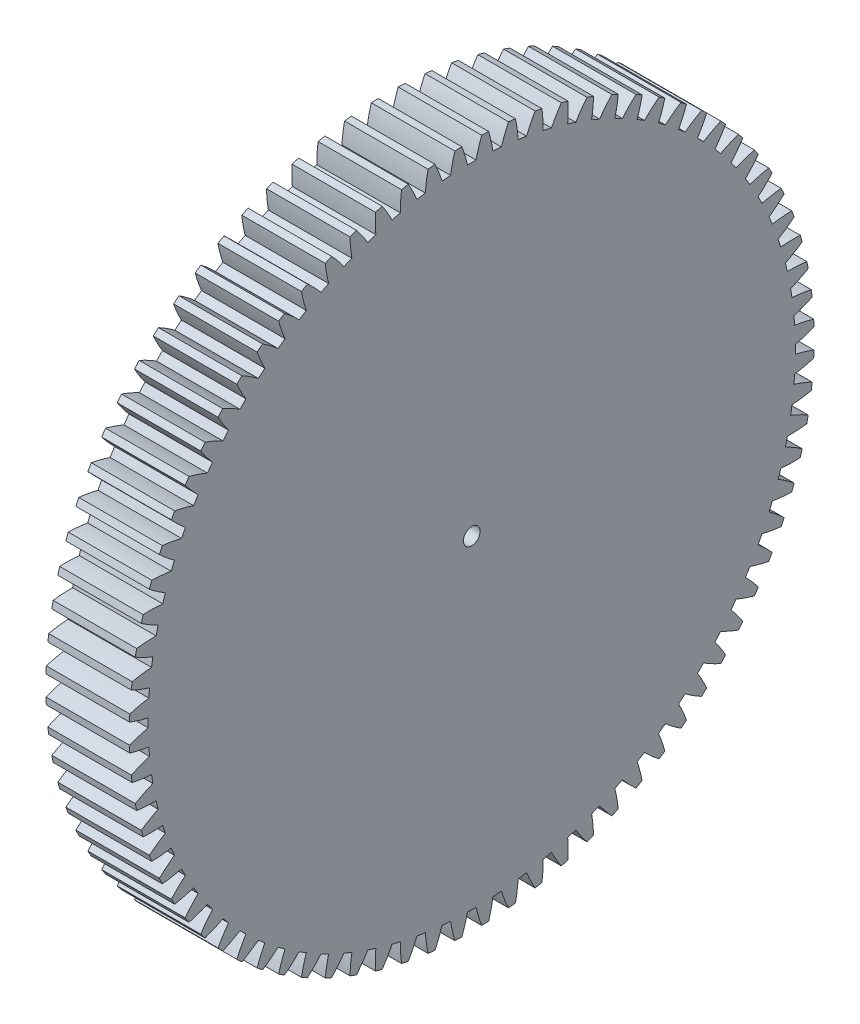
SolidWorks part; units mm, degrees
ref_plane "Plane1" through (0, 0, 0) normal (0, 0, 1) x (1, 0, 0)
ref_plane "Plane2" through (0, 0, 0) normal (0, 1, 0) x (1, 0, 0)
ref_plane "Plane3" through (0, 0, 0) normal (1, 0, 0) x (0, 0, -1)
sketch "HoldingSke" plane through (0, 0, 0) normal (0, 1, 0) x (1, 0, 0)
  line L0 (0, 0) -> (0.1158, -0.6565)
  line L1 (-15, 0) -> (100, 0) construction
  line L2 (0, 0) -> (-2.1039, 2.3779)
  line L3 (0, 0) -> (-11.863, 4.5341)
  line L4 (0, 0) -> (1.4996, 8.5048)
  line L5 (0, 0) -> (-46.8476, -17.4728)
  line L6 (0, 0) -> (-12.4344, -8.3896)
  line L7 (-2.1039, 2.3779) -> (8.6586, 51.2059)
  line L8 (-76.2, 54.61) -> (-75.7, 54.61)
  line L9 (-67.7845, 28.3722) -> (-49.3413, 33.142)
  line L10 (-76.2, 71.12) -> (104.1128, 71.12)
  line L11 (0, 0) -> (-15, 0)
  line L12 (-76.2, 101.6) -> (-76.147, 101.6)
  line L13 (24.9733, 27.94) -> (52.9518, 28.4284)
  line L14 (24.9733, 27.94) -> (24.9743, 27.94)
  line L15 (24.9733, 27.94) -> (100.4006, 29.5858)
  line L16 (-63.627, -1.5) -> (-12.827, -1.5)
  circle A0 centre (0, 0) radius 1.5
  circle A1 centre (0, 0) radius 37.5
  circle A2 centre (0, 0) radius 37.5
  circle A3 centre (0, 0) radius 1.5
  dimension "MHD" = 75
  dimension "Hub_dia" = 75
  dimension "Bore" = 3
  dimension "MBD" = 3
  dimension "Num_teeth" = 80
  dimension "Pitch" = 0.6667
  dimension "Overall_len" = 50
  dimension "Show_teeth" = 80
  dimension "Thickness" = 15
  dimension "OAL" = 50.0001
  dimension "T_dim" = 0.5
  dimension "Ap" = 14.5
  dimension "H" = 19.05
  dimension "Pitch_radius" = 180.3128
  dimension "Width" = 15
  dimension "Backlash" = 0.053
  dimension "Addendum_fac" = 1
  dimension "Dedendum_fac" = 1.25
  dimension "Clearance_fac" = 0.25
  dimension "Dedendum_add" = 0.001
  dimension "Module" = 1.5
sketch "BasProSke" plane through (0, 0, 0) normal (0, 1, 0) x (1, 0, 0)
  line L0 (-10, 0) -> (60, 0) construction
  line L1 (0, 0) -> (0, 61.5)
  line L2 (0, 0) -> (15, 0)
  line L3 (15, 0) -> (15, 61.5)
  line L4 (15, 61.5) -> (0, 61.5)
  dimension "Thickness" = 15
  dimension "Diameter" = 123
revolve "Base-Revolve" add sketch "BasProSke" angle 360 about L0
sketch "TooCutSke" plane through (0, 0, 0) normal (1, 0, 0) x (0, 0, -1)
  line L1 (0, 0) -> (0, 107) construction
  line L2 (0, 0) -> (-1.2708, 59.9865) construction
  line L3 (0, 0) -> (-4.7104, 119.8879) construction
  line L4 (-1.2708, 59.9865) -> (-2.3552, 59.9439) construction
  arc A0 (0.768, 58.1189) -> (-0.768, 58.1189) centre (0, 0) ccw
  arc A1 (1.8001, 61.4991) -> (-1.8001, 61.4991) centre (0, 0) ccw
  circle A2 centre (0, 0) radius 60 construction
  circle A3 centre (0, 0) radius 58.0889 construction
  arc A4 (-0.768, 58.1189) -> (-1.8001, 61.4991) centre (-24.1755, 52.8191) ccw
  arc A5 (1.8001, 61.4991) -> (0.768, 58.1189) centre (24.1755, 52.8191) ccw
  dimension "Root_dia" = 116.248
  dimension "Overcut_dia" = 123.0508
  dimension "Pitch_dia" = 120
  dimension "Base_dia" = 116.1777
  dimension "Flank_rad" = 24
  dimension "Half_ang" = 2.25
  dimension "Half_CT" = 1.0853
extrude "ToothCut" cut sketch "TooCutSke" along normal through all
fillet "Breaks" [suppressed] radius 0.03
fillet "RootFillets" [suppressed] radius 0.376
pattern_circular "TeethCuts" count 80 over 360 about axis through (0, 0, 0) along (1, 0, 0) of "ToothCut", "RootFillets", "Breaks"
sketch "HubNeaOneSke" plane through (0, 0, 0) normal (-1, 0, 0) x (0, 0, 1)
  circle A0 centre (0, 0) radius 37.5
  dimension "Diameter" = 75
extrude "HubNearOne" [suppressed] add sketch "HubNeaOneSke" along normal blind 35.0001
sketch "HubNeaBotSke" plane through (0, 0, 0) normal (-1, 0, 0) x (0, 0, 1)
  circle A0 centre (0, 0) radius 37.5
  dimension "Diameter" = 75
extrude "HubNearBoth" [suppressed] add sketch "HubNeaBotSke" along normal blind 17.5
ref_plane "FarPln" through (15, 0, 0) normal (1, 0, 0) x (0, 0, -1)
sketch "HubFarSke" plane through (15, 0, 0) normal (1, 0, 0) x (0, 0, -1)
  circle A0 centre (0, 0) radius 37.5
  dimension "Diameter" = 75
extrude "HubFar" [suppressed] add sketch "HubFarSke" along normal blind 17.5
sketch "BorSke" plane through (0, 0, 0) normal (1, 0, 0) x (0, 0, -1)
  circle A0 centre (0, 0) radius 1.5
  dimension "Diameter" = 3
extrude "Bore" cut sketch "BorSke" along normal mid plane 100.0001
sketch "KeySke" plane through (0, 0, 0) normal (1, 0, 0) x (0, 0, -1)
  line L0 (-0.6, 0) -> (-0.6, 2)
  line L1 (-0.6, 2) -> (0.6, 2)
  line L2 (0.6, 2) -> (0.6, 0)
  line L3 (0, 0) -> (0, 34) construction
  line L4 (-0.6, 0) -> (0.6, 0)
  dimension "Offset" = 2
  dimension "Width" = 1.2
extrude "Keyway" [suppressed] cut sketch "KeySke" along normal mid plane 100.0001
pattern_circular "Keyway2" [suppressed] count 2 every 90 about axis through (-10, 0, 0) along (1, 0, 0)
equation "' \"Module@HoldingSke\" = 6.35"
equation "' \"Num_teeth@HoldingSke\" = 12"
equation "' \"Ap@HoldingSke\" =  20"
equation "' \"Ap@HoldingSke\" = 20"
equation "' \"Width@HoldingSke\" = 0.5 * 25.4"
equation "' \"Hub_dia@HoldingSke\"= 1 * 25.4"
equation "' \"Hub_dia@HoldingSke\" = 1 * 25.4"
equation "' \"Overall_len@HoldingSke\" = 1.0 * 25.4"
equation "' \"Bore@HoldingSke\" = 0.75 * 25.4"
equation "' \"T_dim@HoldingSke\" = 0.1 * 25.4"
equation "' \"Width@KeySke\" = 0.25 * 25.4"
equation "' \"Show_teeth@HoldingSke\" = 13"
equation "' \"Backlash@HoldingSke\" = 0.009 * 25.4"
equation "' \"Addendum_fac@HoldingSke\" = 1.0"
equation "' \"Dedendum_fac@HoldingSke\" = 1.25"
equation "' \"Dedendum_add@HoldingSke\" = 0.00005 * 25.4"
equation "' \"Clearance_fac@HoldingSke\" = 0.25"
equation "\"Pitch@HoldingSke\" = 1 / \"Module@HoldingSke\""
equation "\"Overcut_dia@TooCutSke\" = (\"Num_teeth@HoldingSke\" + 2 * \"Addendum_fac@HoldingSke\") / \"Pitch@HoldingSke\" + 0.002 * 25.4"
equation "\"Pitch_dia@TooCutSke\" = \"Num_teeth@HoldingSke\" / \"Pitch@HoldingSke\""
equation "\"Base_dia@TooCutSke\" = \"Num_teeth@HoldingSke\" / \"Pitch@HoldingSke\" * cos((\"Ap@HoldingSke\"  * 3.14159265 / 180))"
equation "\"Root_dia@TooCutSke\" = (\"Num_teeth@HoldingSke\" + 2) / \"Pitch@HoldingSke\" - 2 * (\"Addendum_fac@HoldingSke\" + \"Dedendum_fac@HoldingSke\") / \"Pitch@HoldingSke\" - \"Dedendum_add@HoldingSke\" * 2"
equation "\"Half_ang@TooCutSke\" = 180 / \"Num_teeth@HoldingSke\""
equation "\"Half_CT@TooCutSke\" = \"Num_teeth@HoldingSke\" / \"Pitch@HoldingSke\" * sin((3.14159265 / 2 / \"Num_teeth@HoldingSke\")) / 2 - 7 * \"Backlash@HoldingSke\" / 4"
equation "\"Flank_rad@TooCutSke\" = \"Num_teeth@HoldingSke\" / \"Pitch@HoldingSke\" / 5"
equation "\"Radius@RootFillets\" = \"Clearance_fac@HoldingSke\" / \"Pitch@HoldingSke\" + \"Dedendum_add@HoldingSke\""
equation "\"Break_rad@Breaks\" = 0.02 / \"Pitch@HoldingSke\""
equation "\"Thickness@HoldingSke\" = \"Width@HoldingSke\""
equation "\"OAL@HoldingSke\" = \"Thickness@HoldingSke\""
equation "\"MHD@HoldingSke\" = (\"Num_teeth@HoldingSke\" + 2) / \"Pitch@HoldingSke\" - 2 * (\"Addendum_fac@HoldingSke\" + \"Dedendum_fac@HoldingSke\")  / \"Pitch@HoldingSke\" - \"Dedendum_add@HoldingSke\" * 2"
equation "\"MBD@HoldingSke\" = (\"Num_teeth@HoldingSke\" + 2) / \"Pitch@HoldingSke\" - 2 * (\"Addendum_fac@HoldingSke\" + \"Dedendum_fac@HoldingSke\")  / \"Pitch@HoldingSke\" - \"Dedendum_add@HoldingSke\" * 2 - 0.002 * 25.4"
equation "\"MHD@HoldingSke\" = ((sgn( \"MHD@HoldingSke\" - \"Hub_dia@HoldingSke\" )-1)*( \"MHD@HoldingSke\" - \"Hub_dia@HoldingSke\" ))/-2+ \"Hub_dia@HoldingSke\""
equation "\"MBD@HoldingSke\" = ((sgn( \"MBD@HoldingSke\" - \"Bore@HoldingSke\" )-1)*( \"MBD@HoldingSke\" - \"Bore@HoldingSke\" ))/-2+ \"Bore@HoldingSke\""
equation "\"OAL@HoldingSke\" = ((sgn( \"OAL@HoldingSke\" - \"Overall_len@HoldingSke\" )+1)*( \"OAL@HoldingSke\" - \"Overall_len@HoldingSke\" ))/2 + \"Overall_len@HoldingSke\" + 0.000002 * 25.4"
equation "\"Num_teeth@TeethCuts\" = int( \"Show_teeth@HoldingSke\" ) + 1"
equation "\"Num_teeth@TeethCuts\" = ((sgn( \"Num_teeth@TeethCuts\" - \"Num_teeth@HoldingSke\" )-1)*( \"Num_teeth@TeethCuts\" - \"Num_teeth@HoldingSke\" ))/-2+ \"Num_teeth@HoldingSke\""
equation "\"Num_teeth@TeethCuts\" = ((sgn( \"Num_teeth@TeethCuts\" - 2.0)+1)*( \"Num_teeth@TeethCuts\" - 2.0))/2 +2.0"
equation "\"Angle@TeethCuts\" = 360.0 / \"Num_teeth@HoldingSke\""
equation "\"Diameter@BasProSke\" = (\"Num_teeth@HoldingSke\" + 2 * \"Addendum_fac@HoldingSke\") / \"Pitch@HoldingSke\""
equation "\"Thickness@BasProSke\"  = \"Thickness@HoldingSke\""
equation "' \"Fillet_rad@BasProSke\" =  \"Thickness@HoldingSke\" * 0.05"
equation "' \"Fillet_rad@BasProSke\" = \"Thickness@HoldingSke\" * 0.05"
equation "\"MHD@HoldingSke\" = ((sgn( \"MHD@HoldingSke\" - \"Root_dia@TooCutSke\" )-1)*( \"MHD@HoldingSke\" - \"Root_dia@TooCutSke\" ))/-2+ \"Root_dia@TooCutSke\""
equation "\"Diameter@HubNeaOneSke\" = \"MHD@HoldingSke\""
equation "\"Length@HubNearOne\" = \"OAL@HoldingSke\" - \"Thickness@BasProSke\""
equation "\"Diameter@HubNeaBotSke\" = \"MHD@HoldingSke\""
equation "\"Length@HubNearBoth\" = ( \"OAL@HoldingSke\" - \"Thickness@BasProSke\" ) / 2.0"
equation "\"Thickness@FarPln\" = \"Thickness@BasProSke\""
equation "\"Diameter@HubFarSke\" = \"MHD@HoldingSke\""
equation "\"Length@HubFar\" = ( \"OAL@HoldingSke\" - \"Thickness@BasProSke\" ) / 2.0"
equation "\"Diameter@BorSke\" = \"MBD@HoldingSke\""
equation "\"D1@Bore\" = \"OAL@HoldingSke\" * 2.0"
equation "\"D1@Keyway\" = \"OAL@HoldingSke\" * 2.0"
equation "\"Offset@KeySke\" = \"T_dim@HoldingSke\" + \"MBD@HoldingSke\" / 2.0"
